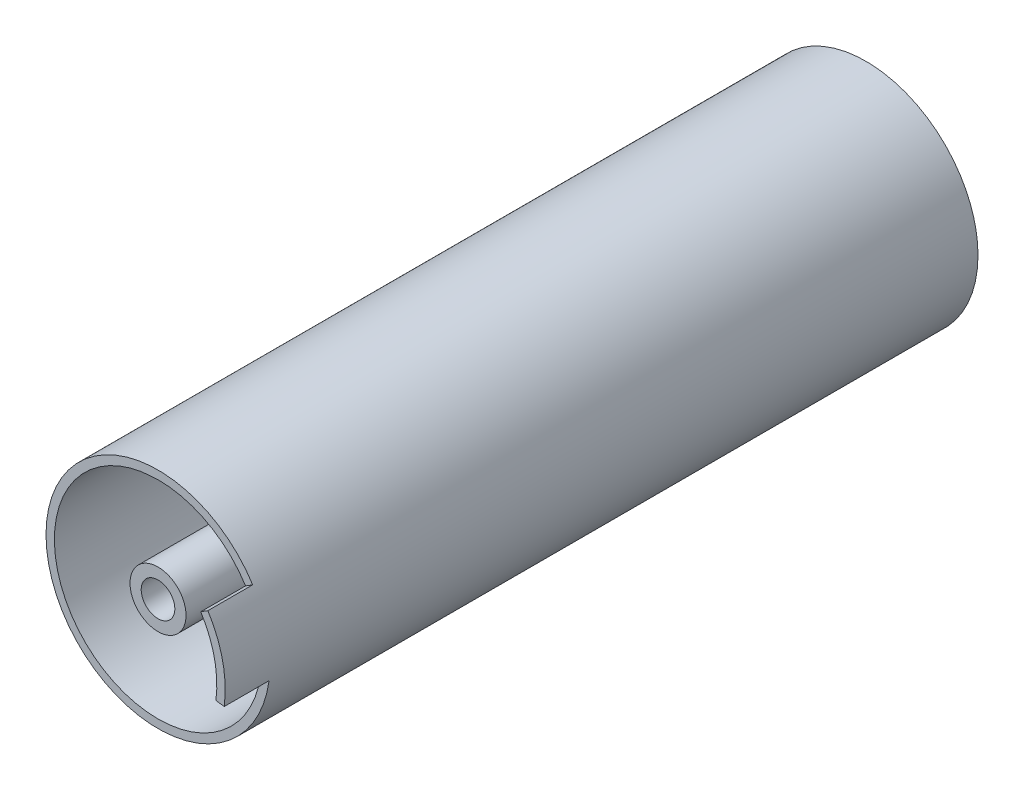
SolidWorks part; units mm, degrees
ref_plane "Спереди" through (0, 0, 0) normal (0, 0, 1) x (1, 0, 0)
ref_plane "Сверху" through (0, 0, 0) normal (0, 1, 0) x (1, 0, 0)
ref_plane "Справа" through (0, 0, 0) normal (1, 0, 0) x (0, 0, -1)
sketch "Эскиз2" plane through (0, 0, 0) normal (0, 0, 1) x (1, 0, 0)
  circle A0 centre (0, 0) radius 20
  circle A1 centre (0, 0) radius 18.5
  dimension "D1" = 40
  dimension "D2" = 37
extrude "Бобышка-Вытянуть1" add sketch "Эскиз2" along normal blind 126.4
sketch "Эскиз5" plane through (0, 0, 0) normal (0, 0, -1) x (-1, 0, 0)
  line L0 (0, 0) -> (0, 18.5) construction
  line L1 (0, 0) -> (2.9901, 18.2568) construction
  line L2 (0, 18.5) -> (0, 9.2195)
  line L3 (2.9901, 18.2568) -> (1.4901, 9.0983)
  circle A0 centre (0, 0) radius 18.5 construction
  arc A1 (0, 18.5) -> (2.9901, 18.2568) centre (0, 0) cw
  arc A2 (1.4901, 9.0983) -> (3.3687, 3.6948) centre (7.4112, 8.1286) ccw
  circle A3 centre (0, 0) radius 3
  arc A4 (-2.7273, 4.1907) -> (3.3687, 3.6948) centre (0, 0) ccw
  arc A5 (0, 9.2195) -> (-2.7273, 4.1907) centre (-6, 9.2195) cw
  point P16 (0, 5)
  dimension "D2" = 5
  dimension "D3" = 6
  dimension "D4" = 6
  dimension "D1" = 3
extrude "Бобышка-Вытянуть3" add sketch "Эскиз5" against normal through all
sketch "Sketch1" plane through (0, 0, 0) normal (0, 0, -1) x (-1, 0, 0)
  line L0 (0, 18.5) -> (2.9901, 18.2568)
  arc A2 (0, 18.5) -> (2.9901, 18.2568) centre (0, 0) ccw
  dimension "D1" = 18.5
extrude "Cut-Extrude1" cut sketch "Sketch1" against normal blind 59
sketch "Sketch2" plane through (0, 0, 126.4) normal (0, 0, 1) x (1, 0, 0)
  line L0 (0, 18.5) -> (-2.9901, 18.2568)
  arc A2 (0, 18.5) -> (-2.9901, 18.2568) centre (0, 0) cw
  dimension "D1" = 18.5
extrude "Cut-Extrude2" cut sketch "Sketch2" against normal blind 59
sketch "Sketch3" plane through (0, 0, 126.4) normal (0, 0, 1) x (1, 0, 0)
  circle A0 centre (0, 0) radius 5
  circle A1 centre (0, 0) radius 3
  dimension "D1" = 10
  dimension "D2" = 6
extrude "Boss-Extrude1" add sketch "Sketch3" against normal offset from surface (58.6 mm away) 0.4 separate body up to face at (-0.7247, 8.9083, 67.4)
sketch "Sketch6" plane through (0, 0, 126.4) normal (0, 0, 1) x (1, 0, 0)
  line L0 (20, 0) -> (0, 0) construction
  line L2 (0, 0) -> (19.8206, -2.6728) construction
  line L3 (0, 0) -> (16.9015, 10.6929) construction
  line L4 (16.9015, 10.6929) -> (15.6339, 9.891)
  line L5 (19.8206, -2.6728) -> (18.3341, -2.4723)
  circle A1 centre (0, 0) radius 20 construction
  arc A3 (16.9015, 10.6929) -> (19.8206, -2.6728) centre (0, 0) cw
  arc A5 (15.6339, 9.891) -> (18.3341, -2.4723) centre (0, 0) cw
  arc A6 (-2.9901, 18.2568) -> (0, 18.5) centre (0, 0) ccw construction
  dimension "D1" = 40
  dimension "D2" = 7.68
extrude "Boss-Extrude4" add sketch "Sketch6" along normal blind 8
